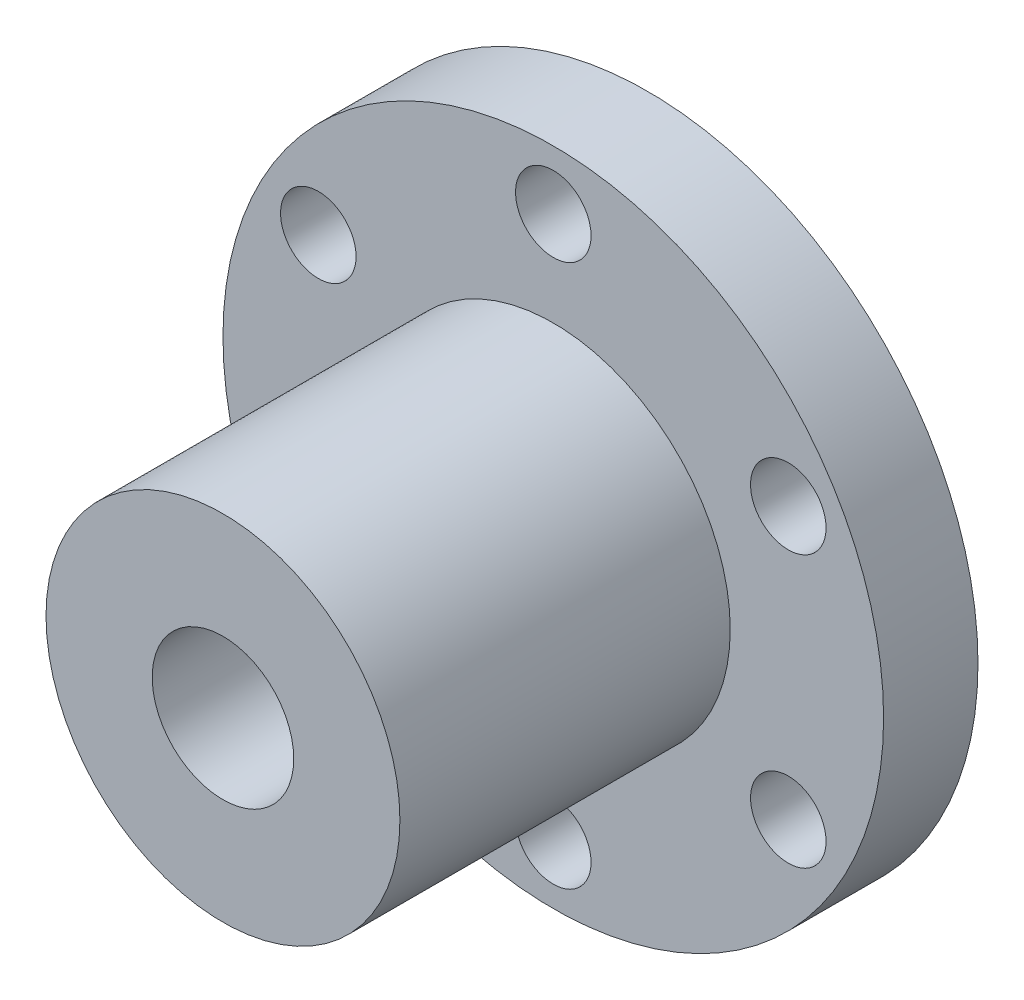
SolidWorks part; units mm, degrees
ref_plane "前视基准面" through (0, 0, 0) normal (0, 0, 1) x (1, 0, 0)
ref_plane "上视基准面" through (0, 0, 0) normal (0, 1, 0) x (1, 0, 0)
ref_plane "右视基准面" through (0, 0, 0) normal (1, 0, 0) x (0, 0, -1)
sketch "草图1" plane through (0, 0, 0) normal (0, 0, 1) x (1, 0, 0)
  circle A0 centre (0, 0) radius 14
  dimension "D1" = 28
extrude "凸台-拉伸1" add sketch "草图1" along normal blind 4
sketch "草图2" plane through (0, 0, 4) normal (0, 0, 1) x (1, 0, 0)
  circle A0 centre (0, 0) radius 7.5
  dimension "D1" = 15
extrude "凸台-拉伸2" add sketch "草图2" along normal blind 14
sketch "草图3" plane through (0, 0, 18) normal (0, 0, 1) x (1, 0, 0)
  circle A0 centre (0, 0) radius 3
  dimension "D1" = 6
extrude "切除-拉伸1" cut sketch "草图3" against normal up to next
sketch "草图4" plane through (0, 0, 4) normal (0, 0, 1) x (1, 0, 0)
  line L0 (0, 0) -> (0, 14) construction
  circle A0 centre (0, 0) radius 14 construction
  circle A1 centre (0, 11.5) radius 1.6
  circle A2 centre (9.9593, 5.75) radius 1.6
  circle A3 centre (9.9593, -5.75) radius 1.6
  circle A4 centre (0, -11.5) radius 1.6
  circle A5 centre (-9.9593, -5.75) radius 1.6
  circle A6 centre (-9.9593, 5.75) radius 1.6
  point P21 (0, 0)
  dimension "D1" = 3.2
  dimension "D2" = 11.5
  dimension "D3" = 6
extrude "切除-拉伸2" cut sketch "草图4" against normal up to next
